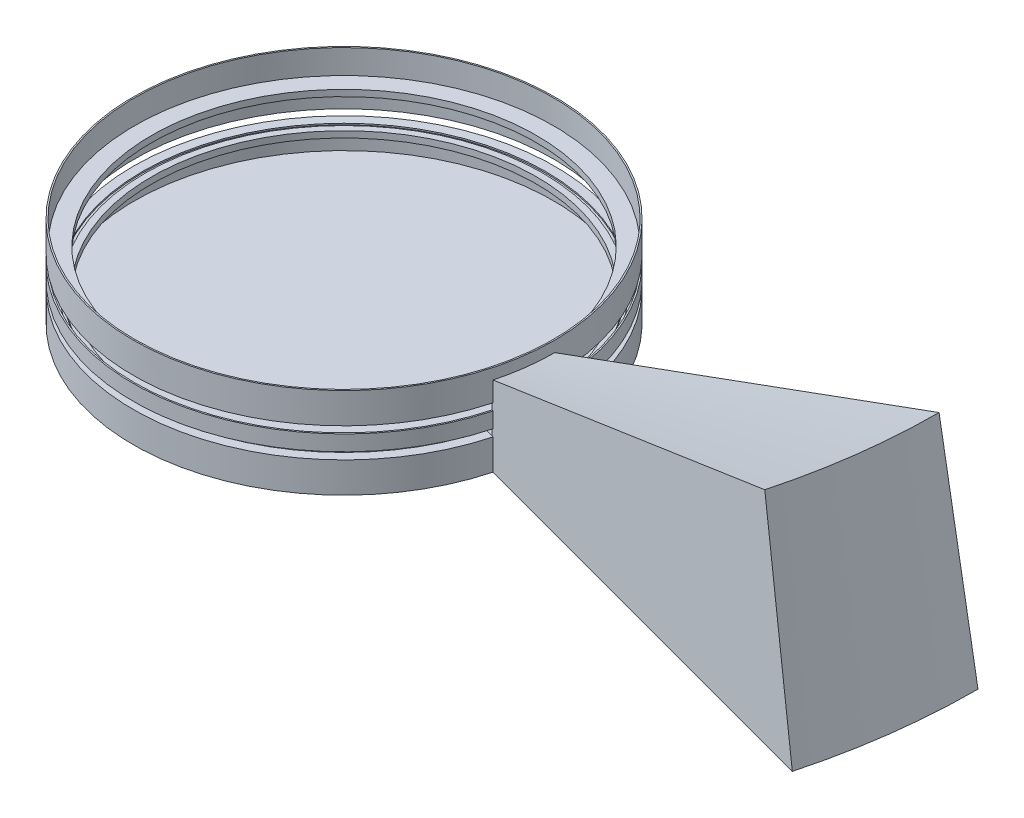
SolidWorks part; units mm, degrees
ref_plane "Front Plane" through (0, 0, 0) normal (0, 0, 1) x (1, 0, 0)
ref_plane "Top Plane" through (0, 0, 0) normal (0, 1, 0) x (1, 0, 0)
ref_plane "Right Plane" through (0, 0, 0) normal (1, 0, 0) x (0, 0, -1)
sketch "Sketch1" plane through (0, 0, 0) normal (0, 1, 0) x (1, 0, 0)
  circle A0 centre (0, 0) radius 300
  circle A1 centre (0, 0) radius 298
extrude "Boss-Extrude2" add sketch "Sketch1" along normal blind 127
sketch "Sketch2" plane through (0, 0, 0) normal (0, 1, 0) x (1, 0, 0)
  circle A0 centre (0, 0) radius 300
extrude "Boss-Extrude3" add sketch "Sketch2" against normal blind 2
sketch "Sketch3" plane through (0, 0, 0) normal (0, 0, 1) x (1, 0, 0)
  line L0 (-300, 127) -> (-300, 73.5) construction
  line L1 (-300, 127) -> (-300, -2) construction
  line L2 (-300, -2) -> (-300, 51.5) construction
  line L3 (0, 51.5) -> (300, 51.5)
  line L5 (300, -2) -> (300, 127) construction
  line L6 (300, 51.5) -> (300, 41.5)
  line L7 (300, 41.5) -> (0, 41.5)
  line L8 (0, 41.5) -> (0, 51.5)
  line L9 (0, 73.5) -> (0, 83.5)
  line L10 (0, 83.5) -> (317.2526, 83.5)
  line L11 (317.2526, 83.5) -> (317.2526, 73.5)
  line L12 (317.2526, 73.5) -> (0, 73.5)
  dimension "D1" = 53.5
  dimension "D2" = 53.5
  dimension "D3" = 10
  dimension "D4" = 10
revolve "Cut-Revolve2" cut sketch "Sketch3" angle 345 about L9
sketch "Sketch4" plane through (0, 0, 0) normal (0, 0, 1) x (1, 0, 0)
  line L1 (-300, -2) -> (300, -2) construction
  line L4 (0, -2) -> (0, 62.8563) construction
  line L6 (845.4273, 308.6304) -> (900, 0)
  line L7 (300, 109.5176) -> (300, 0)
  line L8 (300, 0) -> (900, 0)
  line L9 (300, 109.5176) -> (845.4273, 308.6304)
sketch "Sketch6" plane through (0, 0, 0) normal (0, 1, 0) x (1, 0, 0)
  circle A0 centre (0, 0) radius 300
revolve "Revolve-Thin1" add sketch "Sketch4" angle 15 about L4
sketch "Sketch8" plane through (0, 0, 0) normal (-0.2588, 0, 0.9659) x (0.9659, 0, 0.2588)
  line L0 (300, -2) -> (300, 111.6467)
  line L1 (300, 111.6467) -> (846.9815, 311.3269)
  line L2 (846.9815, 311.3269) -> (902.3847, -2)
  line L3 (902.3847, -2) -> (300, -2)
  line L4 (0, 0) -> (0, 94.4502) construction
revolve "Revolve4" add sketch "Sketch8" angle 0.127 about L4
sketch "Sketch9" plane through (0, 0, 0) normal (0, 0, 1) x (1, 0, 0)
  line L0 (0, 51.5) -> (300, 51.5)
  line L1 (-300, 51.5) -> (300, 51.5) construction
  line L3 (298, 41.5) -> (-298, 41.5) construction
  line L4 (300, 41.5) -> (-300, 41.5) construction
  line L5 (298, 41.5) -> (0, 41.5)
  line L6 (0, 41.5) -> (0, 51.5)
  line L7 (0, 73.5) -> (0, 83.5)
  line L8 (298, 73.5) -> (-298, 73.5) construction
  line L9 (-300, 83.5) -> (300, 83.5) construction
  line L10 (0, 83.5) -> (300, 83.5)
  line L11 (300, 83.5) -> (300, 109.5176) construction
  line L12 (300, 83.5) -> (300, 73.5)
  line L13 (300, 73.5) -> (0, 73.5)
  line L14 (0, 0) -> (0, 123.4252) construction
  line L15 (300, 51.5) -> (300, 41.5)
  line L16 (300, 41.5) -> (298, 41.5)
revolve "Cut-Revolve4" cut sketch "Sketch9" angle 13.5 about L14
sketch "Sketch11" plane through (0, 127, 0) normal (0, 1, 0) x (1, 0, 0)
  circle A1 centre (0, 0) radius 298 construction
  circle A2 centre (0, 0) radius 298 construction
  point P1 (298, 0)
sketch "Sketch12" plane through (0, 0, 0) normal (0, 0, 1) x (1, 0, 0)
  line L0 (298, 83.5) -> (298, 92.5)
  line L1 (298, 92.5) -> (274, 92.5)
  line L2 (274, 92.5) -> (274, 83.5)
  line L3 (-300, 83.5) -> (300, 83.5) construction
  line L4 (274, 83.5) -> (285, 83.5)
  line L5 (285, 83.5) -> (285, 85.5)
  line L6 (285, 85.5) -> (276, 85.5)
  line L7 (276, 85.5) -> (276, 90.5)
  line L8 (276, 90.5) -> (296, 90.5)
  line L9 (296, 90.5) -> (296, 85.5)
  line L10 (296, 85.5) -> (289, 85.5)
  line L11 (289, 85.5) -> (289, 83.5)
  line L12 (289, 83.5) -> (298, 83.5)
  line L13 (298, 78.5) -> (253.8052, 78.5) construction
  line L14 (276, 39.5) -> (276, 34.5)
  line L15 (287, 39.5) -> (287, 41.5)
  line L16 (296, 34.5) -> (296, 39.5)
  line L29 (283, 41.5) -> (283, 39.5)
  line L36 (287, 41.5) -> (298, 41.5)
  line L37 (298, 46.5) -> (253.8052, 46.5) construction
  line L39 (296, 39.5) -> (287, 39.5)
  line L40 (276, 34.5) -> (296, 34.5)
  line L41 (274, 32.5) -> (274, 41.5)
  line L42 (274, 41.5) -> (283, 41.5)
  line L44 (298, 41.5) -> (298, 32.5)
  line L45 (283, 39.5) -> (276, 39.5)
  line L47 (298, 32.5) -> (274, 32.5)
  line L51 (0, 0) -> (0, 135.6004) construction
  point P2 (276, 88)
  point P13 (0, 0)
  point P19 (298, 51.5)
  point P20 (0, 0)
  point P21 (0, 0)
  point P22 (0, 0)
  dimension "D1" = 2
  dimension "D3" = 2
  dimension "D4" = 20
  dimension "D5" = 2
  dimension "D6" = 2
  dimension "D7" = 2
  dimension "D8" = 4
  dimension "D9" = 9
  dimension "D10" = 5
  dimension "D11" = 5
  dimension "D12" = 9
  dimension "D13" = 2
  dimension "D14" = 9
  dimension "D15" = 2
  dimension "D16" = 4
  dimension "D17" = 20
  dimension "D18" = 2
  dimension "D19" = 2.8284
  dimension "D20" = 20
revolve "Revolve5" add sketch "Sketch12" angle 360 about L51
sketch "Sketch14" plane through (0, 0, 0) normal (0, 0, 1) x (1, 0, 0)
  line L1 (0, 85.5135) -> (0, 127)
  line L2 (0, 127) -> (298, 127)
  line L3 (298, 127) -> (298, 6.8401)
  line L4 (298, 6.8401) -> (0, 6.8401)
  line L5 (0, 6.8401) -> (0, 127)
revolve "Cut-Revolve5" cut sketch "Sketch14" angle 15 about L5
sketch "Sketch15" plane through (0, 0, 0) normal (0, 0, 1) x (1, 0, 0)
  line L0 (289, 83.5) -> (298, 83.5)
  line L1 (298, 83.5) -> (298, 92.5)
  line L2 (298, 92.5) -> (274, 92.5)
  line L3 (274, 92.5) -> (274, 83.5)
  line L4 (274, 83.5) -> (285, 83.5)
  line L5 (285, 83.5) -> (285, 85.5)
  line L6 (285, 85.5) -> (276, 85.5)
  line L7 (276, 85.5) -> (276, 90.5)
  line L8 (276, 90.5) -> (296, 90.5)
  line L9 (296, 90.5) -> (296, 85.5)
  line L10 (296, 85.5) -> (289, 85.5)
  line L11 (289, 85.5) -> (289, 83.5)
  line L39 (287, 41.5) -> (298, 41.5)
  line L40 (298, 41.5) -> (298, 32.5)
  line L41 (298, 32.5) -> (274, 32.5)
  line L42 (274, 41.5) -> (274, 32.5) construction
  line L43 (274, 32.5) -> (274, 41.5)
  line L44 (274, 41.5) -> (283, 41.5)
  line L45 (283, 41.5) -> (283, 39.5)
  line L46 (283, 39.5) -> (276, 39.5)
  line L47 (276, 39.5) -> (276, 34.5)
  line L48 (276, 34.5) -> (296, 34.5)
  line L49 (296, 34.5) -> (296, 39.5)
  line L50 (296, 39.5) -> (287, 39.5)
  line L51 (287, 39.5) -> (287, 41.5)
  line L52 (0, 0) -> (0, 217.8249)
revolve "Revolve6" add sketch "Sketch15" angle 10 about L52
